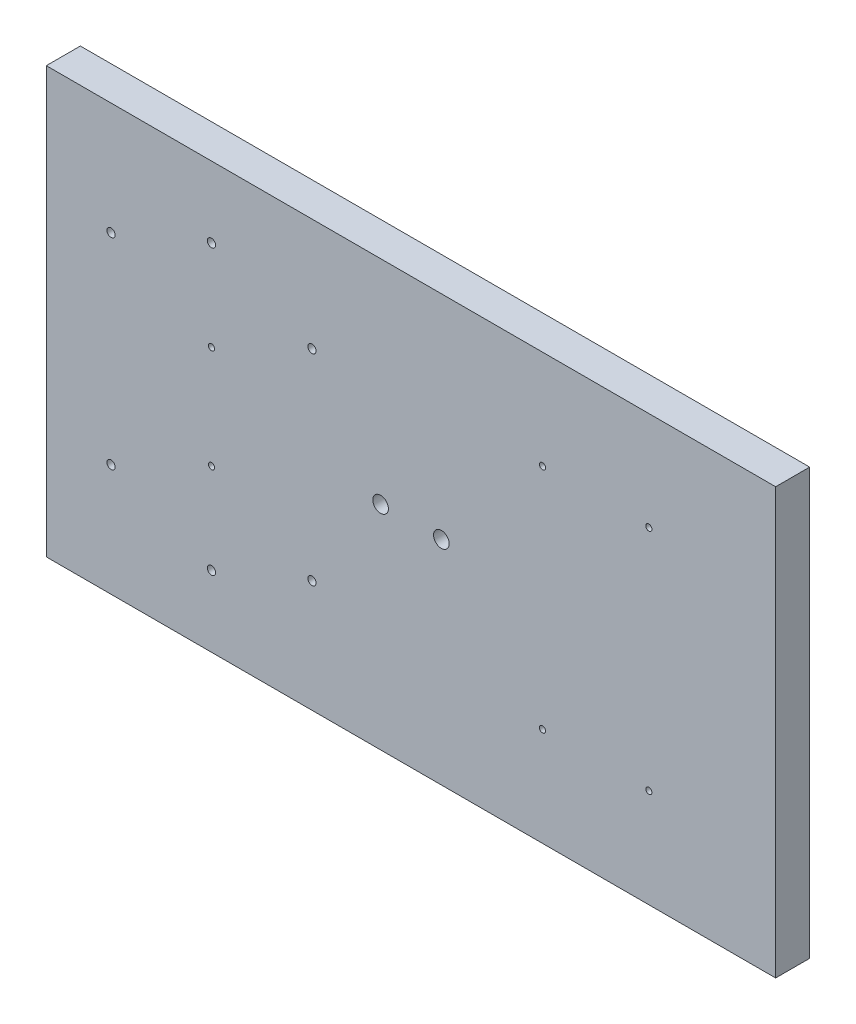
SolidWorks part; units mm, degrees
material "1060 Alloy"
ref_plane "Front Plane" through (0, 0, 0) normal (0, 0, 1) x (1, 0, 0)
ref_plane "Top Plane" through (0, 0, 0) normal (0, 1, 0) x (1, 0, 0)
ref_plane "Right Plane" through (0, 0, 0) normal (1, 0, 0) x (0, 0, -1)
sketch "Sketch1" plane through (0, 0, 0) normal (0, 0, 1) x (1, 0, 0)
  line L1 (-152.4, -88.9) -> (152.4, -88.9)
  line L2 (-152.4, -88.9) -> (-152.4, 88.9)
  line L3 (-152.4, 88.9) -> (152.4, 88.9)
  line L4 (152.4, -88.9) -> (152.4, 88.9)
  line L5 (-152.4, -88.9) -> (152.4, 88.9) construction
  line L6 (-152.4, 88.9) -> (152.4, -88.9) construction
  point P0 (0, 0)
  dimension "D1" = 304.8
  dimension "D2" = 177.8
extrude "Boss-Extrude1" add sketch "Sketch1" along normal blind 14.224
hole_wizard "Tap Drill for #8-32 Tap1" positions "Sketch3" profile "Sketch5" hole size "#8-32" standard "ANSI Inch"
sketch "Sketch3" plane through (0, 0, 14.224) normal (0, 0, 1) x (1, 0, 0)
  point P0 (-41.39, 41.985)
  point P3 (-41.39, -41.985)
  point P6 (-125.36, -41.985)
  point P9 (-125.36, 41.985)
  point P30 (-83.375, 59.2455)
  point P33 (-83.375, -59.2455)
sketch "Sketch5" plane through (-41.39, 41.985, 14.224) normal (1, 0, 0) x (0, -1, 0)
  line L0 (0, 0) -> (0, 8.9118)
  line L1 (0, 8.9118) -> (1.7272, 7.874)
  line L2 (1.7272, 7.874) -> (1.7272, 0)
  line L5 (1.7272, 0) -> (0, 0)
  line L10 (0, 8.9118) -> (-1.7272, 7.874) construction
  line L11 (0, -6.35) -> (0, 107.95) construction
  dimension "Hole Dia." = 3.4544
  dimension "Hole Depth" = 7.874
  dimension "Drill Angle" = 118
hole_wizard "Tap Drill for #5-40 Tap1" positions "Sketch6" profile "Sketch7" hole size "#5-40" standard "ANSI Inch"
sketch "Sketch6" plane through (0, 0, 14.224) normal (0, 0, 1) x (1, 0, 0)
  point P0 (-83.375, 21.5)
  point P3 (-83.375, -21.5)
  point P13 (54.9507, 47.625)
  point P15 (99.4007, 47.625)
  point P17 (99.4007, -47.625)
  point P19 (54.9507, -47.625)
sketch "Sketch7" plane through (-83.375, 21.5, 14.224) normal (1, 0, 0) x (0, -1, 0)
  line L0 (0, 0) -> (0, 8.6485)
  line L1 (0, 8.6485) -> (1.289, 7.874)
  line L2 (1.289, 7.874) -> (1.289, 0)
  line L5 (1.289, 0) -> (0, 0)
  line L10 (0, 8.6485) -> (-1.2891, 7.874) construction
  line L11 (0, -6.35) -> (0, 107.95) construction
  dimension "Hole Dia." = 2.5781
  dimension "Hole Depth" = 7.874
  dimension "Drill Angle" = 118
sketch "Sketch8" plane through (0, 0, 14.224) normal (0, 0, 1) x (1, 0, 0)
  line L0 (-83.375, 21.5) -> (-83.375, -21.5) construction
  line L1 (-104.875, 0) -> (-61.875, 0) construction
  line L2 (77.1757, 50.8) -> (77.1757, -50.8) construction
  line L3 (51.7757, 50.8) -> (102.5757, 50.8) construction
  line L4 (102.5757, -50.8) -> (51.7757, -50.8) construction
  line L5 (65.173, 0) -> (89.1785, 0) construction
  point P8 (-83.375, 0)
  point P18 (77.1757, 0)
hole_wizard "1/4 Clearance Hole1" positions "Sketch9" profile "Sketch10" hole size "1/4" standard "ANSI Inch" end condition through all
sketch "Sketch9" plane through (0, 0, 0) normal (0, 0, 1) x (1, 0, 0)
  line L0 (-152.4, 88.9) -> (152.4, -88.9) construction
  line L2 (0, 0) -> (12.7, 0) construction
  line L4 (0, 0) -> (-12.7, 0) construction
  point P8 (12.7, 0)
  point P13 (-12.7, 0)
  dimension "D1" = 12.7
sketch "Sketch10" plane through (-12.7, 0, 0) normal (1, 0, 0) x (0, 1, 0)
  line L0 (0, 0) -> (0, 14.224)
  line L1 (0, 14.224) -> (3.2639, 14.224)
  line L2 (3.2639, 14.224) -> (3.2639, 0)
  line L5 (3.2639, 0) -> (0, 0)
  line L11 (0, -6.35) -> (0, 107.95) construction
  dimension "Thru Hole Dia." = 6.5278
  dimension "Thru Hole Depth" = 14.224
